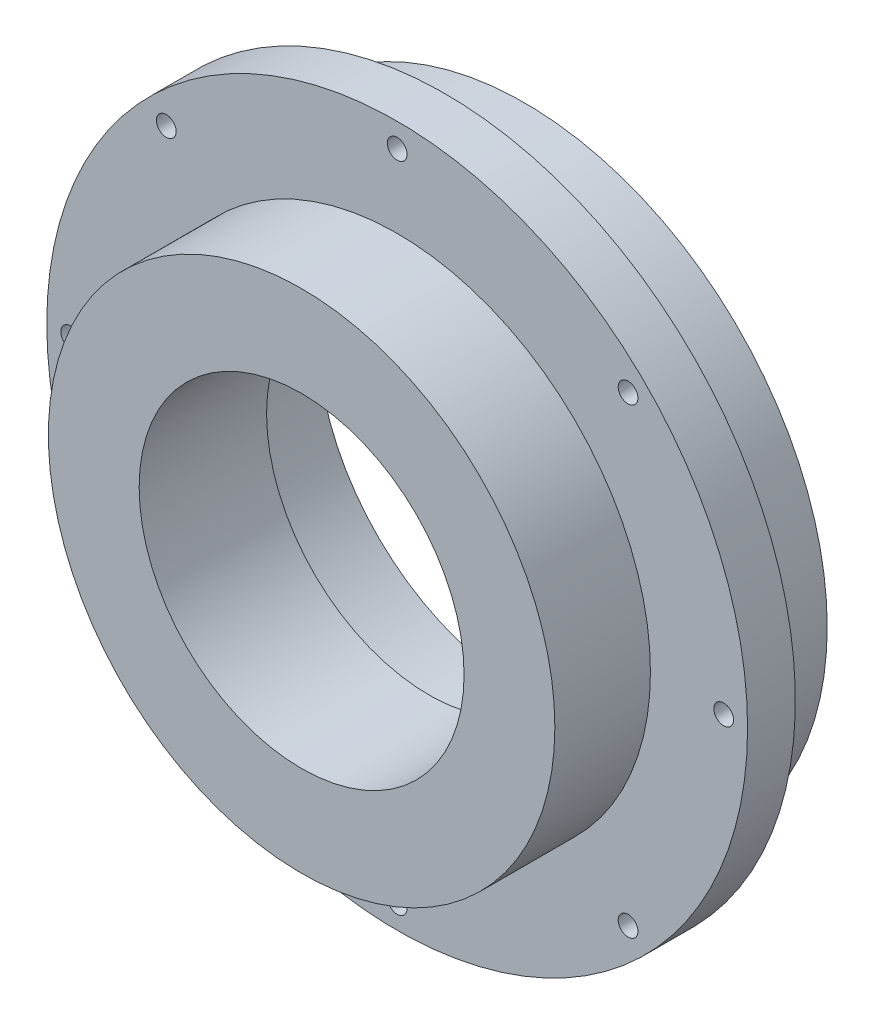
SolidWorks part; units mm, degrees
ref_plane "Ön Düzlem" through (0, 0, 0) normal (0, 0, 1) x (1, 0, 0)
ref_plane "Üst Düzlem" through (0, 0, 0) normal (0, 1, 0) x (1, 0, 0)
ref_plane "Sağ Düzlem" through (0, 0, 0) normal (1, 0, 0) x (0, 0, -1)
sketch "Çizim1" plane through (0, 0, 0) normal (0, 0, 1) x (1, 0, 0)
  circle A0 centre (0, 0) radius 55
  dimension "D1" = 110
extrude "Yükseklik-Ekstrüzyon1" add sketch "Çizim1" along normal mid plane 20
sketch "Çizim2" plane through (0, 0, -10) normal (0, 0, -1) x (-1, 0, 0)
  circle A0 centre (0, 0) radius 47.5
  dimension "D1" = 95
extrude "Kes-Ekstrüzyon1" cut sketch "Çizim2" against normal blind 12.5 flip side to cut
sketch "Çizim3" plane through (0, 0, 2.5) normal (0, 0, -1) x (-1, 0, 0)
  circle A0 centre (0, 0) radius 51.25 construction
  circle A1 centre (0, 51.25) radius 1.55
  dimension "D1" = 102.5
  dimension "D2" = 3.1
extrude "Kes-Ekstrüzyon2" cut sketch "Çizim3" against normal through all
pattern_circular "Dairesel Kaplama1" count 8 over 360 about axis through (0, 0, 0) along (0, 0, 1) of "Kes-Ekstrüzyon2"
sketch "Çizim5" plane through (0, 0, -10) normal (0, 0, -1) x (-1, 0, 0)
  circle A0 centre (0, 0) radius 32.525
  dimension "D1" = 65.05
extrude "Kes-Ekstrüzyon3" cut sketch "Çizim5" against normal blind 15
sketch "Çizim6" plane through (0, 0, 5) normal (0, 0, -1) x (-1, 0, 0)
  circle A0 centre (0, 0) radius 25.5
  dimension "D1" = 51
extrude "Kes-Ekstrüzyon4" cut sketch "Çizim6" against normal through all
sketch "Çizim7" plane through (0, 0, 10) normal (0, 0, 1) x (1, 0, 0)
  circle A0 centre (0, 0) radius 39.75
  circle A1 centre (0, 0) radius 25.5
  dimension "D1" = 79.5
  dimension "D2" = 51
extrude "Yükseklik-Ekstrüzyon2" add sketch "Çizim7" along normal blind 15
sketch "Çizim8" plane through (0, 0, -10) normal (0, 0, -1) x (-1, 0, 0)
  circle A0 centre (16.264, -39.2649) radius 1.5
  circle A1 centre (39.2649, -16.264) radius 1.5
  circle A2 centre (-16.264, -39.2649) radius 1.4645
  circle A3 centre (-39.2649, -16.264) radius 1.5
  circle A4 centre (39.2649, 16.264) radius 1.5
  circle A5 centre (16.264, 39.2649) radius 1.5
  circle A6 centre (-16.264, 39.2649) radius 1.5
  circle A7 centre (-39.2649, 16.264) radius 1.5
extrude "Kes-Ekstrüzyon5" cut sketch "Çizim8" against normal blind 12.5
